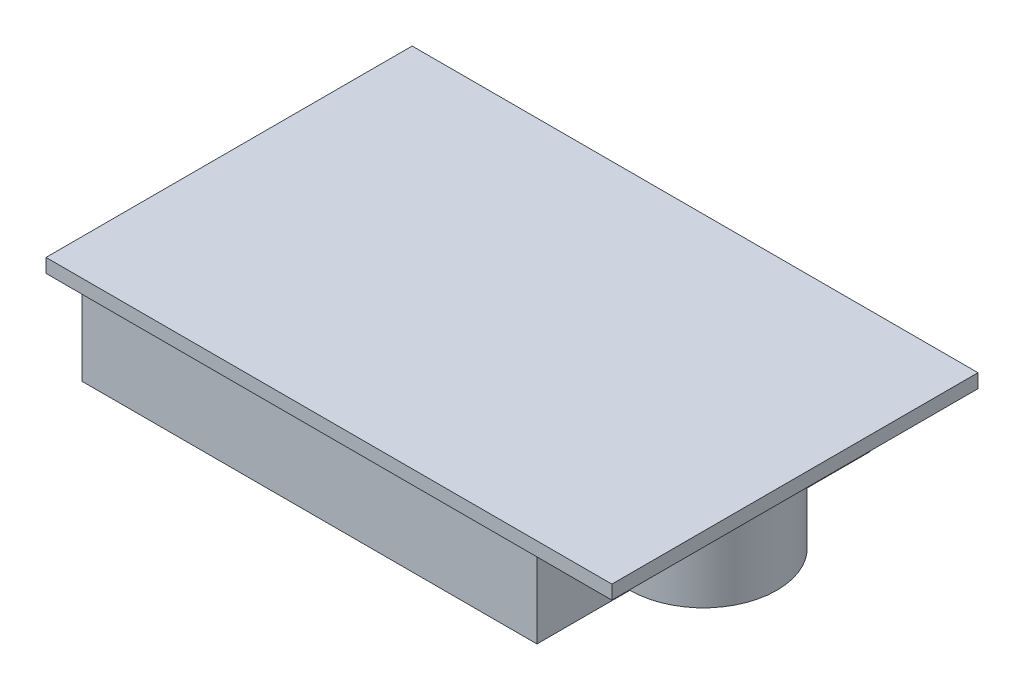
SolidWorks part; units mm, degrees
material "ABS PC"
ref_plane "Front" through (0, 0, 0) normal (0, 0, 1) x (1, 0, 0)
ref_plane "Top" through (0, 0, 0) normal (0, 1, 0) x (1, 0, 0)
ref_plane "Right" through (0, 0, 0) normal (1, 0, 0) x (0, 0, -1)
sketch "Szkic1" plane through (0, 0, 0) normal (0, 1, 0) x (1, 0, 0)
  line L1 (-29.316, -4.202) -> (52.684, -4.202)
  line L2 (-29.316, -4.202) -> (-29.316, 55.798)
  line L3 (-29.316, 55.798) -> (52.684, 55.798)
  line L5 (52.684, 55.798) -> (52.684, 39.048)
  line L6 (52.684, 12.548) -> (52.684, -4.202)
  arc A2 (52.684, 12.548) -> (52.684, 39.048) centre (52.684, 25.798) ccw
  dimension "D1" = 60
  dimension "D2" = 82
extrude "Dodanie-wyciągnięcie1" add sketch "Szkic1" along normal blind 16.6
sketch "Szkic2" plane through (0, 16.6, 0) normal (0, 1, 0) x (1, 0, 0)
  line L0 (-32.816, -16.5101) -> (-32.816, 78.0358) construction
  line L1 (-29.316, 55.798) -> (-29.316, -4.202) construction
  line L2 (-32.816, 25.798) -> (83.7229, 25.798) construction
  line L3 (-32.816, -7.202) -> (-32.816, 58.798)
  line L4 (-32.816, 58.798) -> (69.184, 58.798)
  line L5 (69.184, 58.798) -> (69.184, -7.202)
  line L6 (69.184, -7.202) -> (-32.816, -7.202)
  dimension "D2" = 102
  dimension "D1" = 3.5
extrude "Dodanie-wyciągnięcie3" add sketch "Szkic2" along normal blind 2.5
sketch "Szkic4" plane through (0, 0, 0) normal (0, -1, 0) x (1, 0, 0)
  line L1 (-21.7678, -11.3978) -> (-2.1522, -11.3978)
  line L2 (-21.7678, -11.3978) -> (-21.7678, -42.851)
  line L3 (-21.7678, -42.851) -> (-2.1522, -42.851)
  line L4 (-2.1522, -11.3978) -> (-2.1522, -42.851)
extrude "Wytnij-wyciągnięcie2" cut sketch "Szkic4" against normal blind 12.5
sketch "Szkic6" plane through (0, 19.1, 0) normal (0, 1, 0) x (1, 0, 0)
  line L1 (52.2834, 55.4974) -> (-29.9479, 55.4974)
  line L2 (52.2834, 55.4974) -> (52.2834, -4.1447)
  line L3 (52.2834, -4.1447) -> (-29.9479, -4.1447)
  line L4 (-29.9479, 55.4974) -> (-29.9479, -4.1447)
